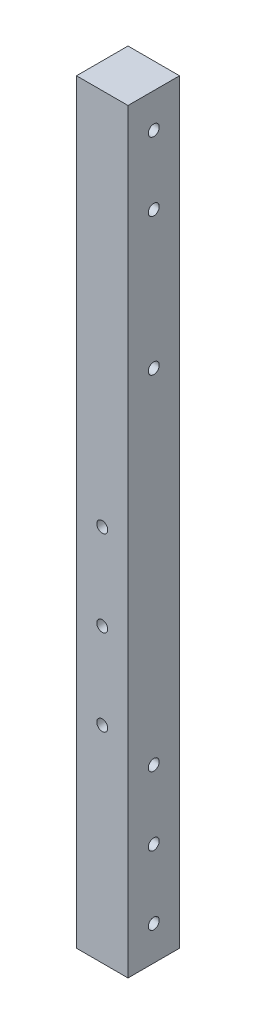
SolidWorks part; units mm, degrees
ref_plane "前视基准面" through (0, 0, 0) normal (0, 0, 1) x (1, 0, 0)
ref_plane "上视基准面" through (0, 0, 0) normal (0, 1, 0) x (1, 0, 0)
ref_plane "右视基准面" through (0, 0, 0) normal (1, 0, 0) x (0, 0, -1)
sketch "草图1" plane through (0, 0, 0) normal (0, 1, 0) x (1, 0, 0)
  line L1 (0, 0) -> (15, 0)
  line L2 (0, 0) -> (0, 15)
  line L3 (0, 15) -> (15, 15)
  line L4 (15, 0) -> (15, 15)
  dimension "D1" = 15
extrude "凸台-拉伸1" add sketch "草图1" along normal blind 220
sketch "草图2" plane through (0, 0, 0) normal (0, 0, 1) x (1, 0, 0)
  line L0 (7.5, -9.7245) -> (7.5, 230.1249) construction
  line L1 (0, 0) -> (15, 0) construction
  circle A0 centre (7.5, 60) radius 1.6
  circle A1 centre (7.5, 85) radius 1.6
  circle A2 centre (7.5, 110) radius 1.6
  dimension "D2" = 25
  dimension "D3" = 25
  dimension "D4" = 60
  dimension "D5" = 3.2
  dimension "D1" = 7.5
extrude "切除-拉伸1" cut sketch "草图2" against normal through all
sketch "草图3" plane through (0, 0, 0) normal (-1, 0, 0) x (0, 0, 1)
  line L0 (0, 220) -> (0, 0) construction
  line L1 (-15, 0) -> (0, 0) construction
  line L2 (-7.5, 242.2996) -> (-7.5, -98.4656) construction
  line L3 (-15, 220) -> (0, 220) construction
  circle A0 centre (-7.5, 50) radius 1.6
  circle A1 centre (-7.5, 10) radius 1.6
  circle A2 centre (-7.5, 30) radius 1.6
  circle A3 centre (-7.5, 210) radius 1.6
  circle A4 centre (-7.5, 190) radius 1.6
  circle A5 centre (-7.5, 150) radius 1.6
  dimension "D1" = 3.2
  dimension "D2" = 7.5
  dimension "D3" = 50
  dimension "D4" = 7.5
  dimension "D5" = 10
  dimension "D6" = 7.5
  dimension "D7" = 20
  dimension "D8" = 10
  dimension "D9" = 20
  dimension "D10" = 100
extrude "切除-拉伸2" cut sketch "草图3" against normal through all both and the other way through all
